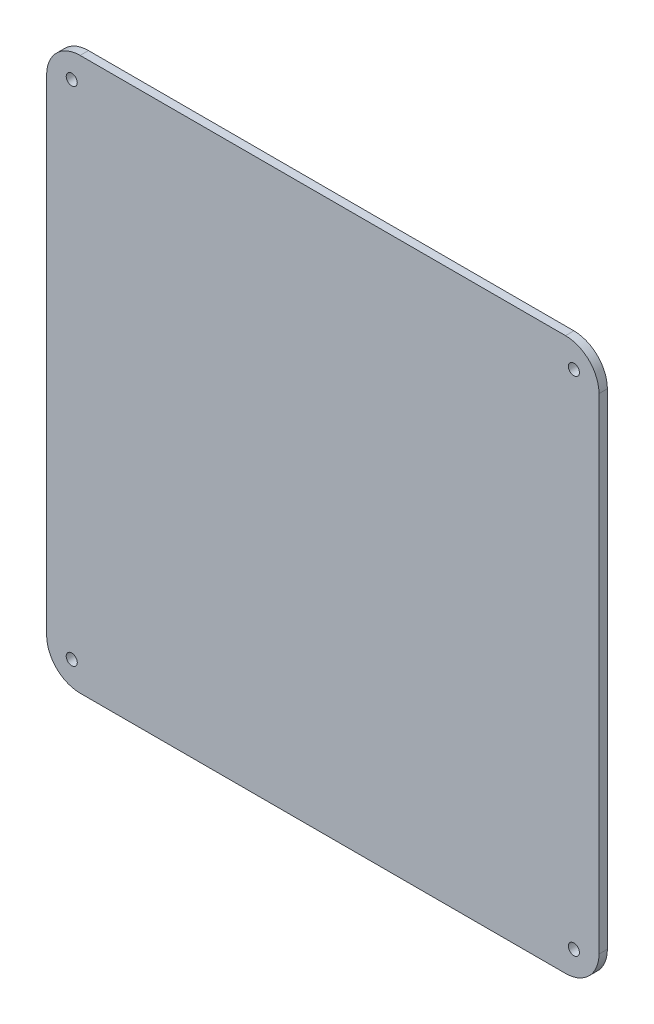
SolidWorks part; units mm, degrees
ref_plane "前视基准面" through (0, 0, 0) normal (0, 0, 1) x (1, 0, 0)
ref_plane "上视基准面" through (0, 0, 0) normal (0, 1, 0) x (1, 0, 0)
ref_plane "右视基准面" through (0, 0, 0) normal (1, 0, 0) x (0, 0, -1)
sketch "草图1" plane through (0, 0, 0) normal (0, 0, 1) x (1, 0, 0)
  line L1 (-43.1288, 308.9425) -> (286.8712, 308.9425)
  line L2 (-43.1288, 308.9425) -> (-43.1288, -21.0575)
  line L3 (-43.1288, -21.0575) -> (286.8712, -21.0575)
  line L4 (286.8712, 308.9425) -> (286.8712, -21.0575)
  dimension "D1" = 330
  dimension "D2" = 330
extrude "凸台-拉伸1" add sketch "草图1" along normal blind 5
fillet "圆角1" radius 20 4 edges at (286.8712, 308.9425, 2.5) (286.8712, -21.0575, 2.5) (-43.1288, -21.0575, 2.5) (-43.1288, 308.9425, 2.5)
sketch "草图2" plane through (0, 0, 0) normal (0, 0, -1) x (-1, 0, 0)
  line L1 (-271.8712, 293.9425) -> (28.1288, 293.9425) construction
  line L2 (-271.8712, 293.9425) -> (-271.8712, -6.0575) construction
  line L3 (-271.8712, -6.0575) -> (28.1288, -6.0575) construction
  line L4 (28.1288, 293.9425) -> (28.1288, -6.0575) construction
  circle A0 centre (28.1288, -6.0575) radius 3.3
  circle A1 centre (-271.8712, -6.0575) radius 3.3
  circle A2 centre (-271.8712, 293.9425) radius 3.3
  circle A3 centre (28.1288, 293.9425) radius 3.3
  dimension "D1" = 6.6
  dimension "D2" = 6.6
  dimension "D3" = 6.6
  dimension "D4" = 6.6
extrude "切除-拉伸1" cut sketch "草图2" against normal blind 10
